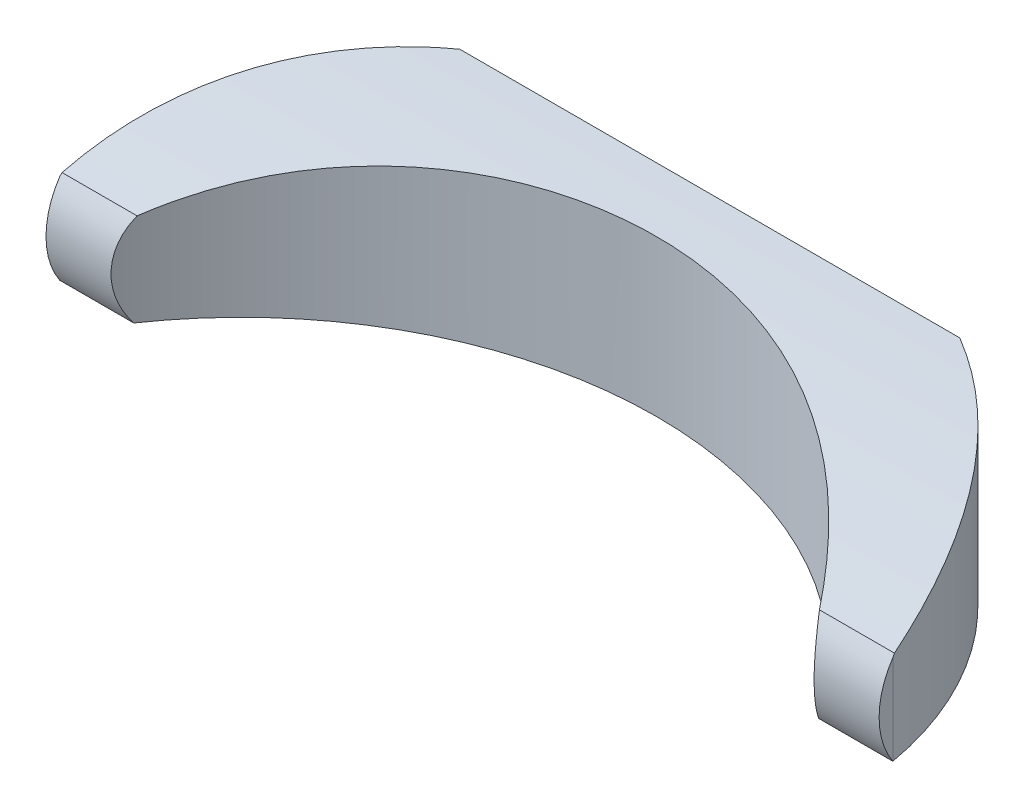
SolidWorks part; units mm, degrees
material "Custom Plastic"
ref_plane "Front Plane" through (0, 0, 0) normal (0, 0, 1) x (1, 0, 0)
ref_plane "Top Plane" through (0, 0, 0) normal (0, 1, 0) x (1, 0, 0)
ref_plane "Right Plane" through (0, 0, 0) normal (1, 0, 0) x (0, 0, -1)
sketch "Sketch2" plane through (0, 0, 0) normal (0, 1, 0) x (1, 0, 0)
  line L1 (-153.6412, 88.3659) -> (346.3588, 88.3659)
  line L2 (-153.6412, 88.3659) -> (-153.6412, -61.6341)
  line L3 (-153.6412, -61.6341) -> (346.3588, -61.6341)
  line L4 (346.3588, 88.3659) -> (346.3588, -61.6341)
  dimension "D1" = 500
  dimension "D2" = 150
extrude "Boss-Extrude1" add sketch "Sketch2" along normal blind 100
sketch "Sketch4" plane through (-153.6412, 0, 0) normal (-1, 0, 0) x (0, 0, 1)
  line L0 (-88.3659, 100) -> (61.6341, 100)
  line L2 (51.7892, 0) -> (61.6341, 0)
  line L3 (61.6341, 100) -> (61.6341, 0) construction
  line L4 (61.6341, 0) -> (61.6341, 50)
  line L7 (61.6341, 100) -> (61.6341, 50)
  arc A0 (-88.3659, 100) -> (50.6177, 55.5188) centre (-173.7079, -406.0259) cw
  arc A2 (51.7892, 0) -> (50.6177, 55.5188) centre (11.8982, 26.93) ccw
extrude "Cut-Extrude1" cut sketch "Sketch4" against normal blind 540
ref_plane "Plane1" through (0, 100, 0) normal (0, -1, 0) x (-1, 0, 0)
sketch "Sketch5" plane through (0, 100, 0) normal (0, -1, 0) x (-1, 0, 0)
  circle A0 centre (-96.3588, -192.841) radius 249.3187
extrude "Cut-Extrude2" cut sketch "Sketch5" along normal blind 560
sketch "Sketch6" plane through (0, 100, 0) normal (0, -1, 0) x (-1, 0, 0)
  line L1 (-346.3588, 88.3659) -> (153.6412, 88.3659) construction
  line L3 (-246.3588, 88.3659) -> (-346.3588, 88.3659)
  line L4 (-346.3588, 88.3659) -> (-346.3588, -50.6177) construction
  line L5 (-346.3588, 88.3659) -> (-346.3588, -51.7892)
  line L6 (53.6412, 88.3659) -> (153.6412, 88.3659)
  line L7 (153.6412, 88.3659) -> (153.6412, -51.7892)
  arc A0 (-346.3588, -51.7892) -> (-246.3588, 88.3659) centre (-149.4049, -86.5625) cw
  arc A1 (53.6412, 88.3659) -> (153.6412, -51.7892) centre (-43.3126, -86.5625) cw
extrude "Cut-Extrude3" cut sketch "Sketch6" along normal blind 560
